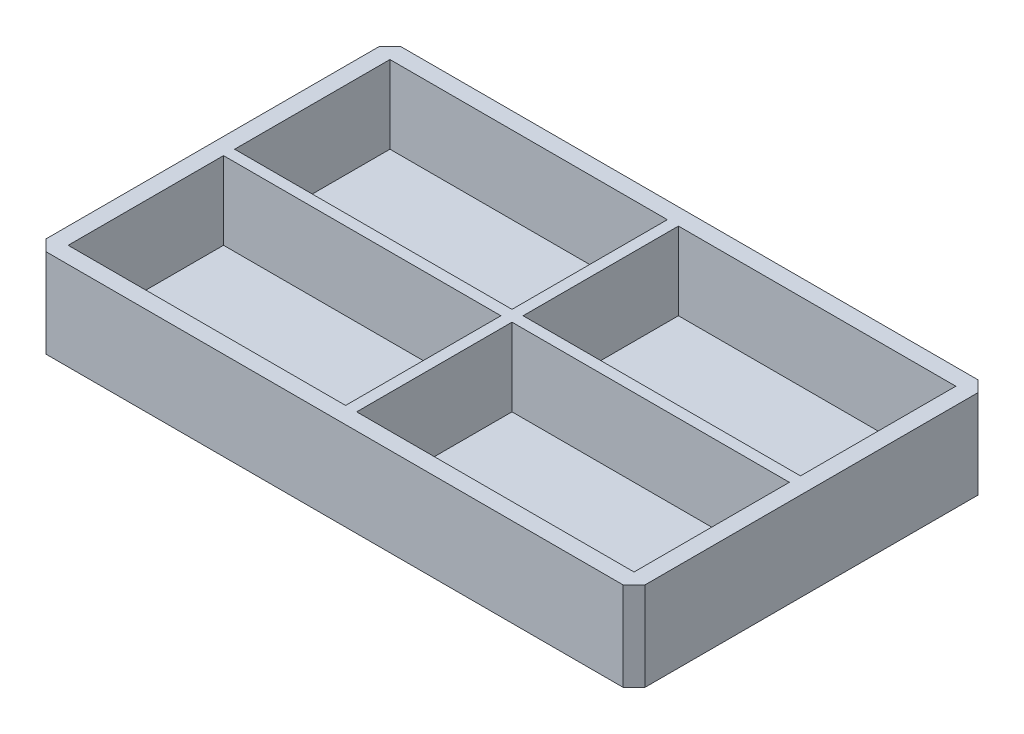
SolidWorks part; units mm, degrees
ref_plane "Front Plane" through (0, 0, 0) normal (0, 0, 1) x (1, 0, 0)
ref_plane "Top Plane" through (0, 0, 0) normal (0, 1, 0) x (1, 0, 0)
ref_plane "Right Plane" through (0, 0, 0) normal (1, 0, 0) x (0, 0, -1)
sketch "Sketch1" plane through (0, 0, 0) normal (0, 1, 0) x (1, 0, 0)
  line L1 (-24.1957, 14.1405) -> (0.8043, 14.1405)
  line L2 (-24.1957, 14.1405) -> (-24.1957, 0.1405)
  line L3 (-24.1957, 0.1405) -> (0.8043, 0.1405)
  line L4 (0.8043, 14.1405) -> (0.8043, 0.1405)
  line L5 (-24.1957, -0.8595) -> (0.8043, -0.8595)
  line L6 (-24.1957, -0.8595) -> (-24.1957, -14.8595)
  line L7 (-24.1957, -14.8595) -> (0.8043, -14.8595)
  line L8 (0.8043, -0.8595) -> (0.8043, -14.8595)
  line L9 (1.8043, 14.1405) -> (26.8043, 14.1405)
  line L10 (1.8043, 14.1405) -> (1.8043, 0.1405)
  line L11 (1.8043, 0.1405) -> (26.8043, 0.1405)
  line L12 (26.8043, 14.1405) -> (26.8043, 0.1405)
  line L13 (1.8043, -0.8595) -> (26.8043, -0.8595)
  line L14 (1.8043, -0.8595) -> (1.8043, -14.8595)
  line L15 (1.8043, -14.8595) -> (26.8043, -14.8595)
  line L16 (26.8043, -0.8595) -> (26.8043, -14.8595)
  line L17 (-25.6957, 15.6405) -> (28.3043, 15.6405)
  line L18 (-25.6957, 15.6405) -> (-25.6957, -16.3595)
  line L19 (-25.6957, -16.3595) -> (28.3043, -16.3595)
  line L20 (28.3043, 15.6405) -> (28.3043, -16.3595)
  point P20 (-11.6957, 14.1405)
  dimension "D1" = 14
  dimension "D2" = 25
  dimension "D3" = 14
  dimension "D4" = 25
  dimension "D5" = 14
  dimension "D6" = 25
  dimension "D7" = 14
  dimension "D8" = 25
  dimension "D9" = 1
  dimension "D10" = 1
  dimension "D11" = 1
  dimension "D12" = 1
  dimension "D13" = 1.5
  dimension "D14" = 1.5
  dimension "D15" = 1.5
  dimension "D16" = 1.5
  dimension "D17" = 0
extrude "Boss-Extrude1" add sketch "Sketch1" along normal blind 7
sketch "Sketch2" plane through (0, 0, 0) normal (0, -1, 0) x (1, 0, 0)
  line L1 (-25.6957, 16.3595) -> (28.3043, 16.3595)
  line L2 (-25.6957, 16.3595) -> (-25.6957, -15.6405)
  line L3 (-25.6957, -15.6405) -> (28.3043, -15.6405)
  line L4 (28.3043, 16.3595) -> (28.3043, -15.6405)
extrude "Boss-Extrude2" add sketch "Sketch2" along normal blind 1
chamfer "Chamfer1" distance 1 angle 45 4 edges at (-25.6957, 3, -15.6405) (-25.6957, 3, 16.3595) (28.3043, 3, -15.6405) (28.3043, 3, 16.3595)
